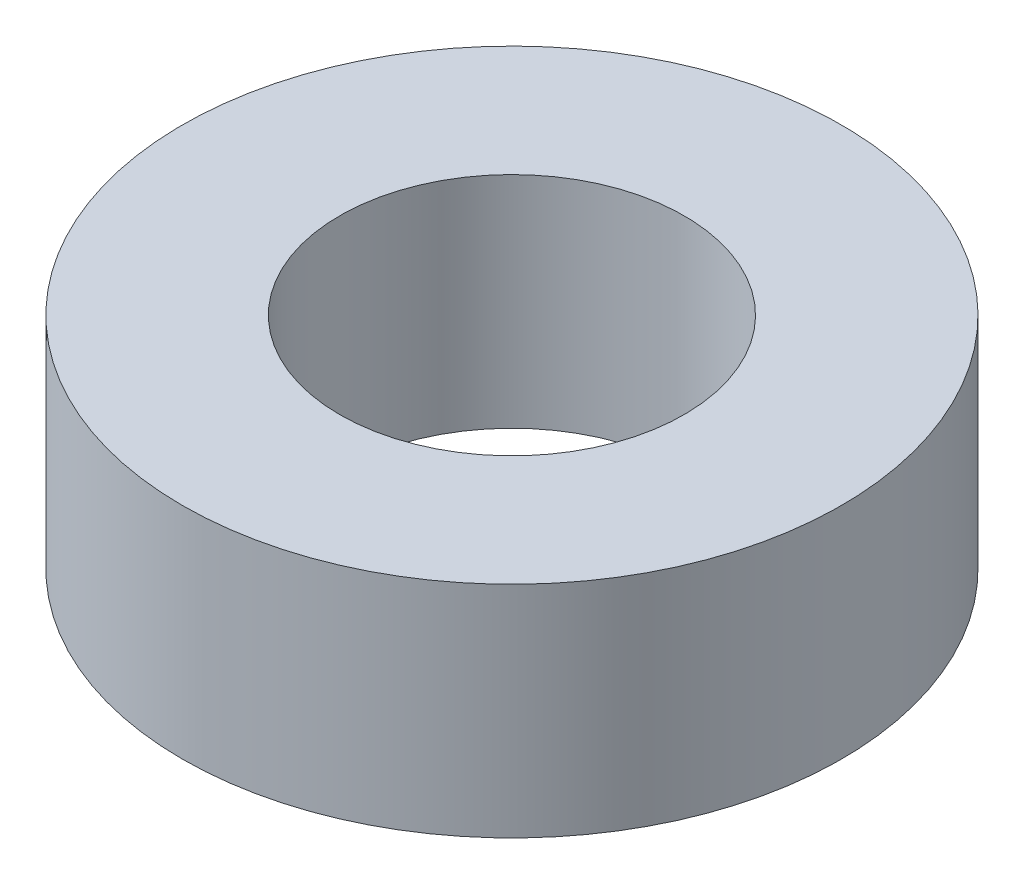
SolidWorks part; units mm, degrees
material "Alum Plate"
ref_plane "Front Plane" through (0, 0, 0) normal (0, 0, 1) x (1, 0, 0)
ref_plane "Top Plane" through (0, 0, 0) normal (0, 1, 0) x (1, 0, 0)
ref_plane "Right Plane" through (0, 0, 0) normal (1, 0, 0) x (0, 0, -1)
other "Bounding Box"
ref_plane "Default Plane" through (-8.9266, -12.7485, 0) normal (-0.1736, 0.9848, 0) x (0.9848, 0.1736, 0)
sketch "Sketch1" plane through (0, 0, 0) normal (0, 1, 0) x (1, 0, 0)
  circle A0 centre (0, 0) radius 2.4892
  circle A1 centre (0, 0) radius 4.7625
  dimension "D1" = 9.525
  dimension "D2" = 4.9784
extrude "Boss-Extrude1" add sketch "Sketch1" along normal mid plane 3.175
